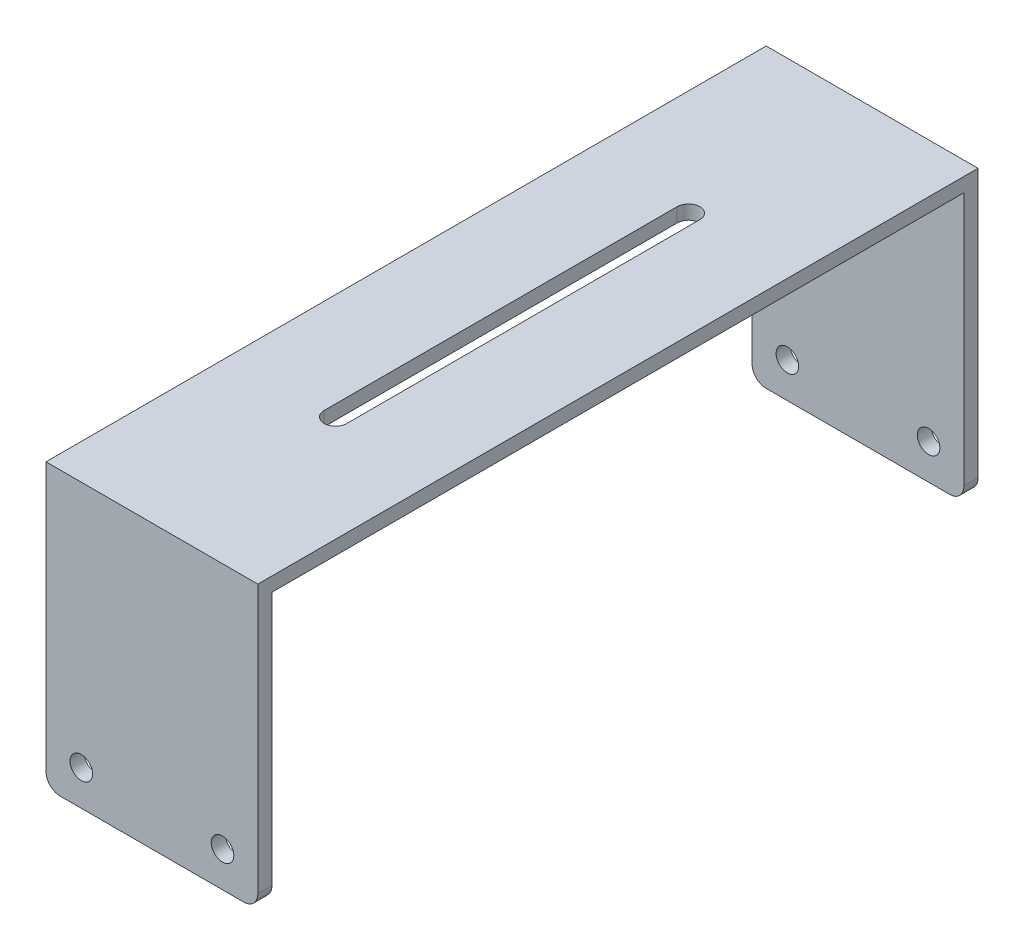
SolidWorks part; units mm, degrees
ref_plane "前视基准面" through (0, 0, 0) normal (0, 0, 1) x (1, 0, 0)
ref_plane "上视基准面" through (0, 0, 0) normal (0, 1, 0) x (1, 0, 0)
ref_plane "右视基准面" through (0, 0, 0) normal (1, 0, 0) x (0, 0, -1)
other "Configuration Table"
sketch "草图1" plane through (0, 0, 0) normal (0, 0, 1) x (1, 0, 0)
  line L1 (0, 0) -> (30, 0)
  line L2 (0, 0) -> (0, 40)
  line L3 (0, 40) -> (30, 40)
  line L4 (30, 0) -> (30, 40)
  circle A0 centre (5, 5) radius 1.6
  circle A1 centre (25, 5) radius 1.6
  dimension "D1" = 20
  dimension "D7" = 3.2
  dimension "D8" = 3.2
  dimension "D2" = 30
  dimension "D3" = 5
  dimension "D4" = 5
  dimension "D5" = 5
  dimension "D6" = 40
extrude "凸台-拉伸1" add sketch "草图1" along normal blind 2
sketch "草图3" plane through (0, 0, 0) normal (0, 0, -1) x (-1, 0, 0)
  line L0 (0, 40) -> (0, 0) construction
  line L1 (-30, 40) -> (0, 40)
  line L2 (-30, 40) -> (-30, 38)
  line L3 (-30, 38) -> (0, 38)
  line L4 (0, 40) -> (0, 38)
  dimension "D1" = 2
extrude "凸台-拉伸2" add sketch "草图3" along normal blind 100
sketch "草图5" plane through (0, 38, 0) normal (0, -1, 0) x (1, 0, 0)
  line L0 (0, -100) -> (0, 0) construction
  line L1 (0, -98) -> (30, -98)
  line L2 (0, -98) -> (0, -100)
  line L3 (0, -100) -> (30, -100)
  line L4 (30, -98) -> (30, -100)
  dimension "D1" = 2
extrude "凸台-拉伸4" add sketch "草图5" along normal blind 38
sketch "草图6" plane through (0, 0, 2) normal (0, 0, 1) x (1, 0, 0)
  circle A0 centre (5, 5) radius 1.6 construction
  circle A1 centre (5, 5) radius 1.6
  circle A2 centre (25, 5) radius 1.6 construction
  circle A3 centre (25, 5) radius 1.6
extrude "切除-拉伸1" cut sketch "草图6" against normal through all
sketch "草图7" plane through (0, 40, 0) normal (0, 1, 0) x (1, 0, 0)
  line L0 (0, 49) -> (-10.7352, 49) construction
  line L1 (0, -2) -> (0, 100) construction
  line L2 (15, 24) -> (15, 74) construction
  line L3 (13.4, 24) -> (13.4, 74)
  line L4 (16.6, 24) -> (16.6, 74)
  line L5 (15, -2) -> (15, 1.6175) construction
  line L6 (30, -2) -> (0, -2) construction
  arc A0 (13.4, 24) -> (16.6, 24) centre (15, 24) ccw
  arc A1 (16.6, 74) -> (13.4, 74) centre (15, 74) ccw
  point P6 (15, 49)
  dimension "D2" = 1.6
  dimension "D1" = 50
extrude "切除-拉伸2" cut sketch "草图7" against normal up to surface (2 mm away) up to face at (15, 38, -49)
fillet "圆角1" radius 2 4 edges at (30, 0, -99) (0, 0, -99) (30, 0, 1) (0, 0, 1)
